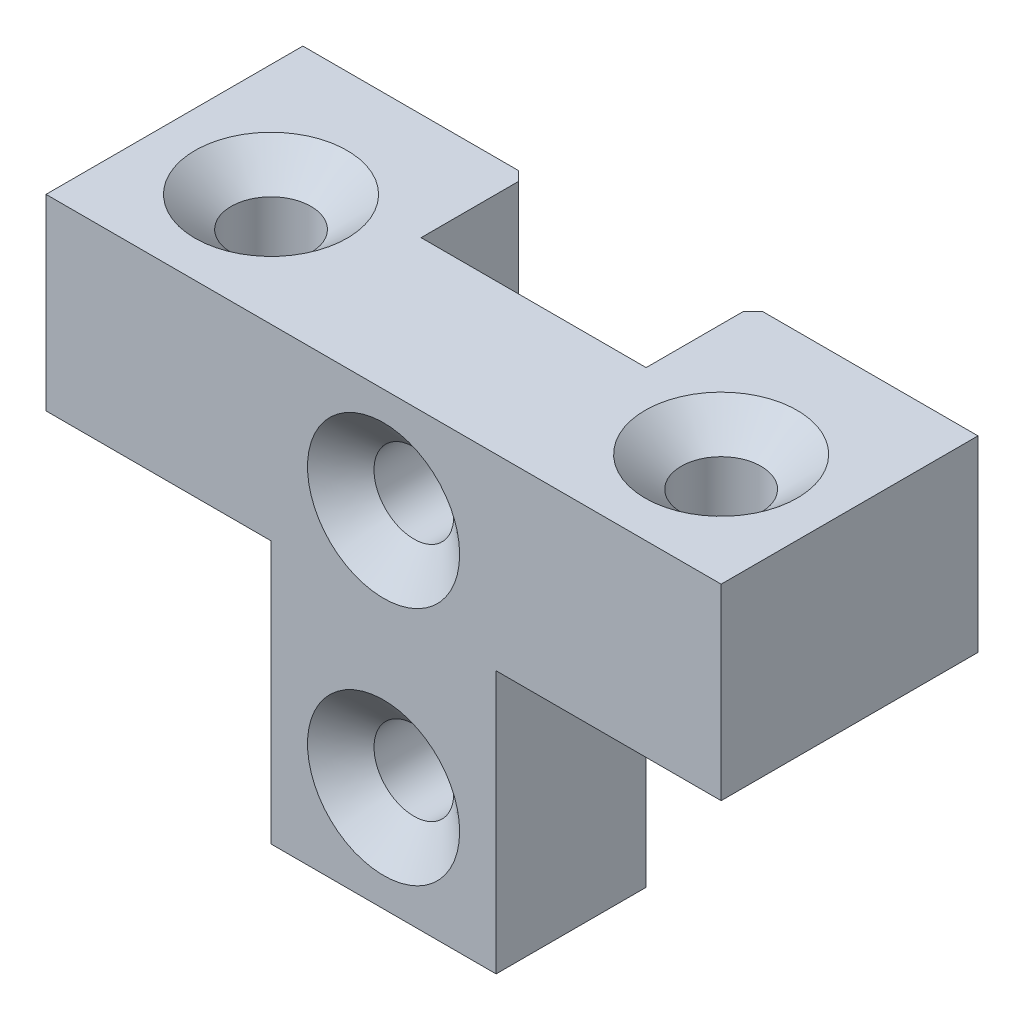
SolidWorks part; units mm, degrees
ref_plane "Front" through (0, 0, 0) normal (0, 0, 1) x (1, 0, 0)
ref_plane "Top" through (0, 0, 0) normal (0, 1, 0) x (1, 0, 0)
ref_plane "Right" through (0, 0, 0) normal (1, 0, 0) x (0, 0, -1)
sketch "Sketch1" plane through (0, 0, 0) normal (0, 0, 1) x (1, 0, 0)
  line L0 (0, 0) -> (22.2463, 0) construction
  line L1 (-28.575, 19.05) -> (28.575, 19.05)
  line L2 (19.05, 29.2913) -> (19.05, -10.8361) construction
  line L3 (9.525, 3.175) -> (19.05, 3.175)
  line L4 (28.575, 19.05) -> (28.575, 3.175)
  line L5 (19.05, 3.175) -> (28.575, 3.175)
  line L6 (0, 19.05) -> (0, -19.05) construction
  line L7 (-9.525, -19.05) -> (9.525, -19.05)
  line L8 (9.525, 3.175) -> (9.525, -19.05)
  line L9 (-9.525, 3.175) -> (-9.525, -19.05)
  line L10 (-9.525, 3.175) -> (-19.05, 3.175)
  line L11 (-19.05, 3.175) -> (-28.575, 3.175)
  line L12 (-28.575, 19.05) -> (-28.575, 3.175)
  dimension "D1" = 9.525
  dimension "D2" = 38.1
  dimension "D3" = 3.175
  dimension "D4" = 19.05
extrude "Boss-Extrude1" add sketch "Sketch1" against normal blind 12.7
hole_wizard "CSK for 1/4 Flat Head Machine Screw (100)1" positions "Sketch2" profile "Sketch3" countersink size "1/4" standard "ANSI Inch" end condition through all
sketch "Sketch2" plane through (0, 0, 0) normal (0, 0, 1) x (1, 0, 0)
  line L0 (0, 10.16) -> (0, -10.16) construction
  point P0 (0, 10.16)
  point P2 (0, -10.16)
  point P7 (0, 0)
  dimension "D1" = 20.32
sketch "Sketch3" plane through (0, 10.16, 0) normal (1, 0, 0) x (0, -1, 0)
  line L0 (0, 0) -> (0, 12.7)
  line L1 (0, 12.7) -> (3.3782, 12.7)
  line L2 (3.3782, 12.7) -> (3.3782, 2.5682)
  line L3 (3.3782, 2.5682) -> (6.4389, 0)
  line L5 (6.4389, 0) -> (0, 0)
  line L6 (-3.3782, 2.5682) -> (-6.4389, 0) construction
  line L11 (0, -6.35) -> (0, 107.95) construction
  dimension "Thru Hole Dia." = 6.7564
  dimension "Thru Hole Depth" = 12.7
  dimension "Near C'Sink Dia." = 12.8778
  dimension "Near C'Sink Angle" = 100
sketch "Sketch7" plane through (0, 19.05, 0) normal (0, 1, 0) x (1, 0, 0)
  line L0 (-28.575, 12.7) -> (-9.525, 12.7) construction
  line L1 (9.525, 12.7) -> (28.575, 12.7) construction
  line L2 (-28.575, 12.7) -> (-9.525, 12.7) construction
  line L3 (9.525, 12.7) -> (28.575, 12.7) construction
  line L4 (-9.525, 12.7) -> (-9.525, 11.1125)
  line L5 (-9.525, 11.1125) -> (9.525, 11.1125)
  line L6 (9.525, 11.1125) -> (9.525, 12.7)
  line L7 (9.525, 12.7) -> (-9.525, 12.7)
  line L8 (28.575, 0) -> (-28.575, 0) construction
  dimension "D1" = 11.1125
extrude "Cut-Extrude1" [suppressed] cut sketch "Sketch7" against normal through all
sketch "Sketch6" plane through (0, 0, -12.7) normal (0, 0, 1) x (1, 0, 0)
  line L0 (-9.525, 3.175) -> (-9.525, 19.05)
  line L1 (28.575, 19.05) -> (-28.575, 19.05) construction
  line L2 (9.525, 3.175) -> (9.525, 19.05)
  line L4 (-28.575, 3.175) -> (-9.525, 3.175) construction
  line L5 (28.575, 3.175) -> (28.575, 19.05) construction
  line L6 (9.525, 3.175) -> (28.575, 3.175) construction
  line L7 (9.525, 19.05) -> (28.575, 19.05)
  line L8 (28.575, 3.175) -> (28.575, 19.05)
  line L9 (9.525, 3.175) -> (28.575, 3.175)
  line L10 (-28.575, 3.175) -> (-28.575, 19.05)
  line L11 (-28.575, 3.175) -> (-9.525, 3.175)
  line L12 (-9.525, 19.05) -> (-28.575, 19.05)
extrude "Boss-Extrude2" add sketch "Sketch6" against normal blind 9.0424
hole_wizard "CSK for 1/4 Flat Head Machine Screw (100)2" positions "Sketch4" profile "Sketch5" countersink size "1/4" standard "ANSI Inch" end condition through all
sketch "Sketch4" plane through (0, 19.05, 0) normal (0, 1, 0) x (1, 0, 0)
  line L0 (-19.05, 9.525) -> (19.05, 9.525) construction
  line L5 (0, 9.525) -> (0, 0) construction
  line L6 (28.575, 0) -> (-28.575, 0) construction
  point P0 (-19.05, 9.525)
  point P2 (19.05, 9.525)
  dimension "D1" = 38.1
  dimension "D2" = 9.525
sketch "Sketch5" plane through (-19.05, 19.05, -9.525) normal (1, 0, 0) x (0, 0, 1)
  line L0 (0, 0) -> (0, 38.1)
  line L1 (0, 38.1) -> (3.3782, 38.1)
  line L2 (3.3782, 38.1) -> (3.3782, 2.5682)
  line L3 (3.3782, 2.5682) -> (6.4389, 0)
  line L5 (6.4389, 0) -> (0, 0)
  line L6 (-3.3782, 2.5682) -> (-6.4389, 0) construction
  line L11 (0, -6.35) -> (0, 107.95) construction
  dimension "Thru Hole Dia." = 6.7564
  dimension "Thru Hole Depth" = 38.1
  dimension "Near C'Sink Dia." = 12.8778
  dimension "Near C'Sink Angle" = 100
chamfer "Chamfer1" distance 0.7937 angle 45 2 edges at (-9.525, 11.1125, -21.7424) (9.525, 11.1125, -21.7424)
